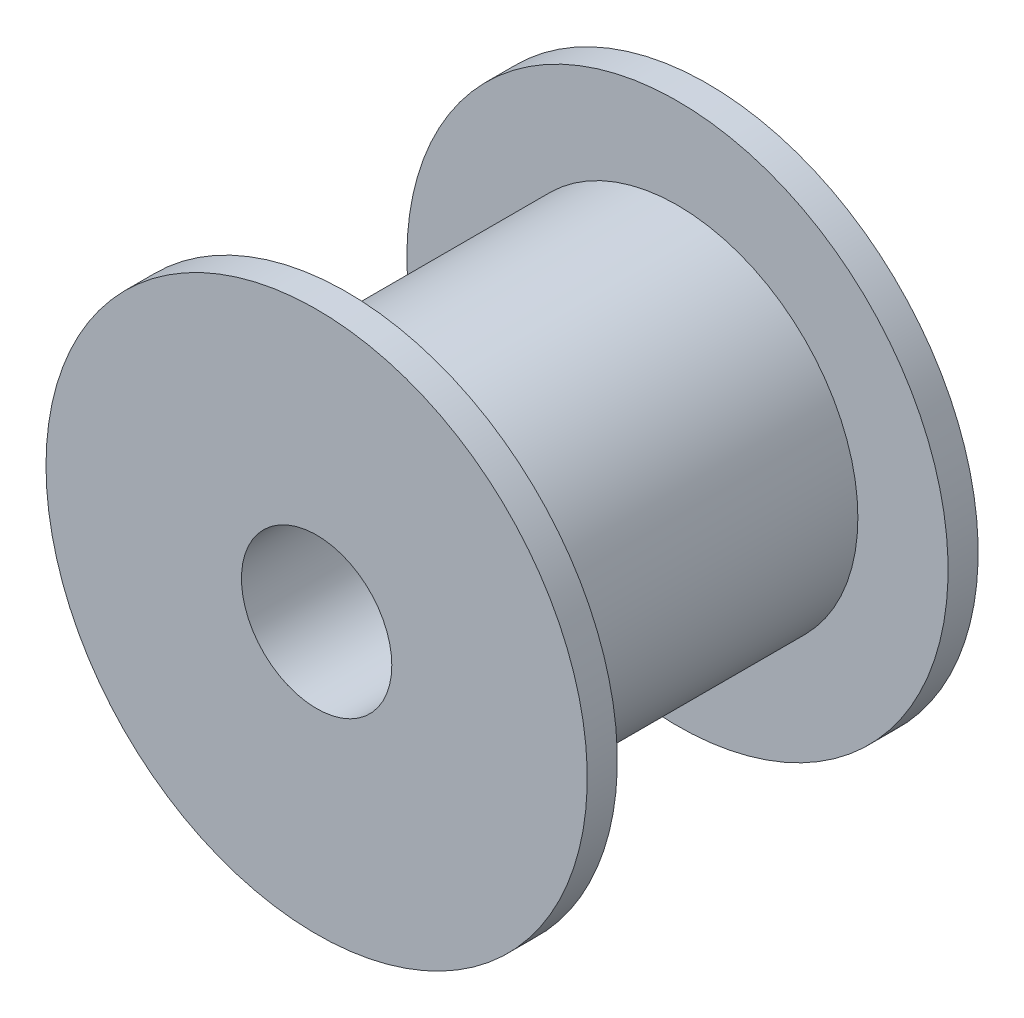
SolidWorks part; units mm, degrees
ref_plane "前视基准面" through (0, 0, 0) normal (0, 0, 1) x (1, 0, 0)
ref_plane "上视基准面" through (0, 0, 0) normal (0, 1, 0) x (1, 0, 0)
ref_plane "右视基准面" through (0, 0, 0) normal (1, 0, 0) x (0, 0, -1)
other "Configuration Table"
sketch "草图1" plane through (0, 0, 0) normal (0, 0, 1) x (1, 0, 0)
  circle A0 centre (0, 0) radius 9
  dimension "D1" = 18
extrude "凸台-拉伸1" add sketch "草图1" along normal blind 13
sketch "草图2" plane through (0, 0, 13) normal (0, 0, 1) x (1, 0, 0)
  circle A0 centre (0, 0) radius 6
  circle A1 centre (0, 0) radius 9
  dimension "D1" = 12
extrude "切除-拉伸1" cut sketch "草图2" against normal blind 11 from offset 1 contours A1 | A0 offset against normal yes
sketch "草图3" plane through (0, 0, 13) normal (0, 0, 1) x (1, 0, 0)
  circle A0 centre (0, 0) radius 2.5
  dimension "D1" = 5
extrude "切除-拉伸2" cut sketch "草图3" against normal through all
